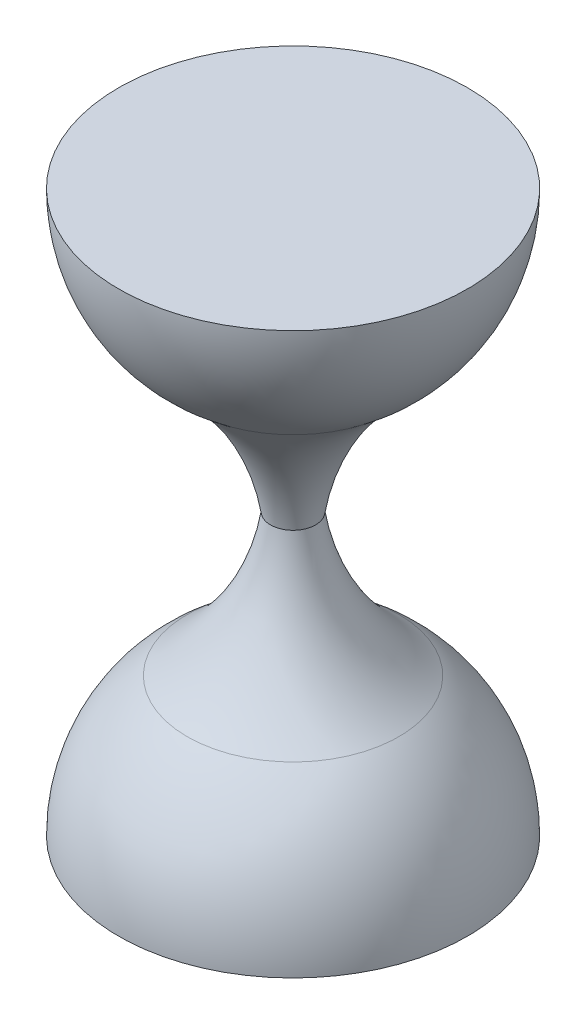
SolidWorks part; units mm, degrees
material "Glass"
ref_plane "Front Plane" through (0, 0, 0) normal (0, 0, 1) x (1, 0, 0)
ref_plane "Top Plane" through (0, 0, 0) normal (0, 1, 0) x (1, 0, 0)
ref_plane "Right Plane" through (0, 0, 0) normal (1, 0, 0) x (0, 0, -1)
sketch "Sketch1" plane through (0, 0, 0) normal (0, 0, 1) x (1, 0, 0)
  line L0 (0, 0) -> (0, 57.15)
  line L1 (0, 57.15) -> (35.56, 57.15)
  line L2 (4.5871, 0) -> (0, 0)
  arc A0 (35.56, 57.15) -> (21.5864, 28.8915) centre (0, 57.15) cw
  arc A1 (21.5864, 28.8915) -> (4.5871, 0) centre (48.5693, -6.4316) ccw
  dimension "D3" = 44.45
  dimension "D1" = 57.15
  dimension "D2" = 35.56
  dimension "D4" = 48.5693
revolve "Revolve1" add sketch "Sketch1" angle 360 about L0
mirror "Mirror1" about plane through (4.5871, 0, 0) normal (0, -1, 0) of "Revolve1"
